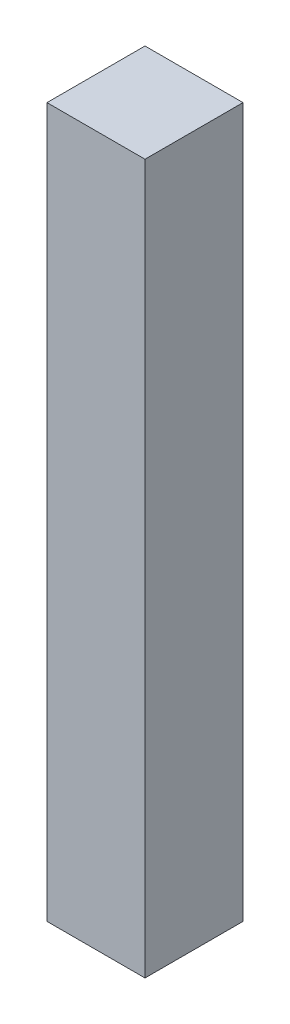
SolidWorks part; units mm, degrees
ref_plane "Front Plane" through (0, 0, 0) normal (0, 0, 1) x (1, 0, 0)
ref_plane "Top Plane" through (0, 0, 0) normal (0, 1, 0) x (1, 0, 0)
ref_plane "Right Plane" through (0, 0, 0) normal (1, 0, 0) x (0, 0, -1)
sketch "Sketch1" plane through (0, 0, 0) normal (0, 1, 0) x (1, 0, 0)
  line L1 (-36.055, 5.2706) -> (-6.055, 5.2706)
  line L2 (-36.055, 5.2706) -> (-36.055, -24.7294)
  line L3 (-36.055, -24.7294) -> (-6.055, -24.7294)
  line L4 (-6.055, 5.2706) -> (-6.055, -24.7294)
  dimension "D1" = 30
  dimension "D2" = 30
extrude "Boss-Extrude1" add sketch "Sketch1" along normal blind 217
